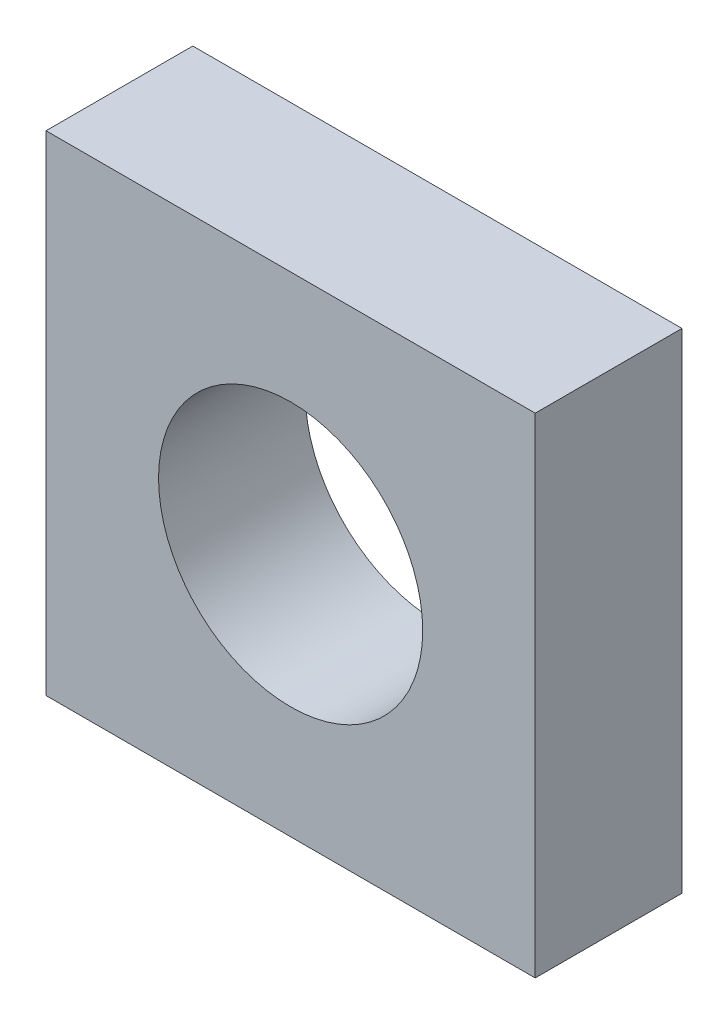
SolidWorks part; units mm, degrees
ref_plane "Alzado" through (0, 0, 0) normal (0, 0, 1) x (1, 0, 0)
ref_plane "Planta" through (0, 0, 0) normal (0, 1, 0) x (1, 0, 0)
ref_plane "Vista lateral" through (0, 0, 0) normal (1, 0, 0) x (0, 0, -1)
sketch "Croquis1" plane through (0, 0, 0) normal (0, 0, 1) x (1, 0, 0)
  line L1 (-7.5, 7.5) -> (7.5, 7.5)
  line L2 (-7.5, 7.5) -> (-7.5, -7.5)
  line L3 (-7.5, -7.5) -> (7.5, -7.5)
  line L4 (7.5, 7.5) -> (7.5, -7.5)
  line L5 (-7.5, 7.5) -> (7.5, -7.5) construction
  line L6 (-7.5, -7.5) -> (7.5, 7.5) construction
  circle A0 centre (0, 0) radius 4.05
  point P0 (0, 0)
  point P8 (9.2642, -14.1351)
  point P9 (0, 0)
  dimension "D1" = 8.1
  dimension "D2" = 15
  dimension "D3" = 15
extrude "Saliente-Extruir1" add sketch "Croquis1" along normal blind 4.5
